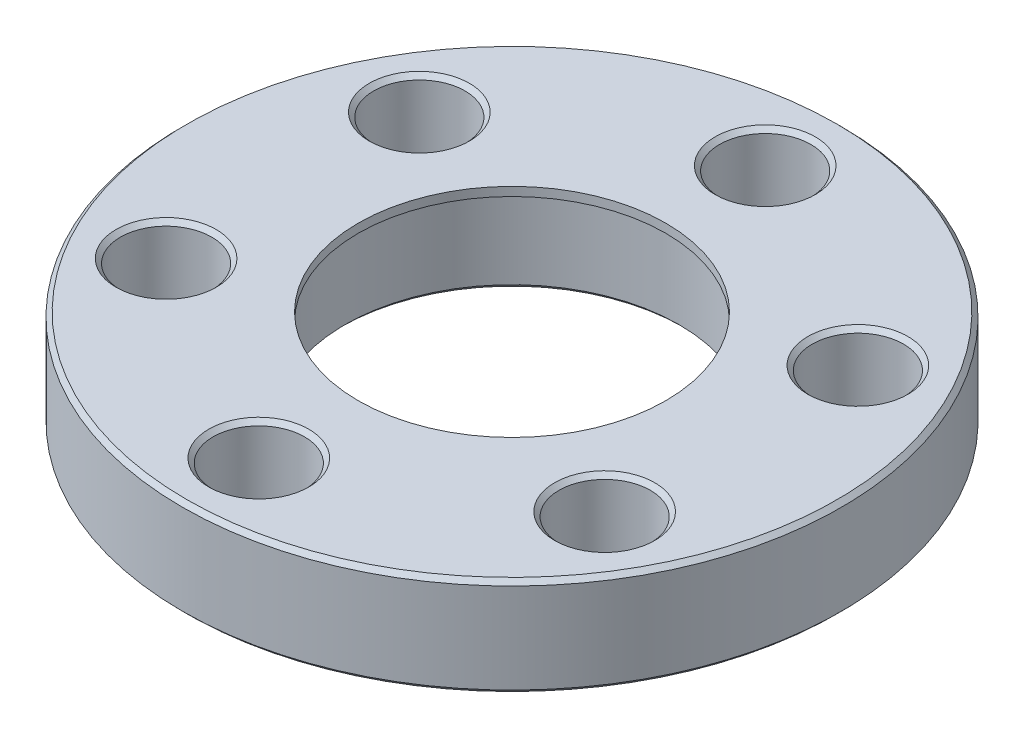
SolidWorks part; units mm, degrees
ref_plane "前视基准面" through (0, 0, 0) normal (0, 0, 1) x (1, 0, 0)
ref_plane "上视基准面" through (0, 0, 0) normal (0, 1, 0) x (1, 0, 0)
ref_plane "右视基准面" through (0, 0, 0) normal (1, 0, 0) x (0, 0, -1)
other "Configuration Table"
sketch "草图1" plane through (0, 0, 0) normal (0, 1, 0) x (1, 0, 0)
  circle A0 centre (0, 0) radius 7
  circle A1 centre (0, 0) radius 15
  circle A2 centre (0, 0) radius 11.525 construction
  circle A3 centre (0, 11.525) radius 2.08
  circle A4 centre (9.9809, 5.7625) radius 2.08
  circle A5 centre (9.9809, -5.7625) radius 2.08
  circle A6 centre (0, -11.525) radius 2.08
  circle A7 centre (-9.9809, -5.7625) radius 2.08
  circle A8 centre (-9.9809, 5.7625) radius 2.08
  point P19 (0, 0)
  dimension "D1" = 14
  dimension "D2" = 30
  dimension "D3" = 23.05
  dimension "D4" = 4.16
  dimension "D5" = 6
extrude "凸台-拉伸1" add sketch "草图1" along normal blind 3.1
sketch "草图2" plane through (0, 0, 0) normal (0, -1, 0) x (-1, 0, 0)
  circle A0 centre (0, 0) radius 7 construction
  circle A1 centre (0, 0) radius 15 construction
  circle A2 centre (0, 0) radius 7
  circle A3 centre (0, 0) radius 15
  circle A4 centre (0, 11.53) radius 0.9
  circle A6 centre (0, 0) radius 11.53 construction
  circle A7 centre (9.9853, 5.765) radius 0.9
  circle A8 centre (9.9853, -5.765) radius 0.9
  circle A9 centre (0, -11.53) radius 0.9
  circle A10 centre (-9.9853, -5.765) radius 0.9
  circle A11 centre (-9.9853, 5.765) radius 0.9
  point P21 (0, 0)
  dimension "D1" = 1.8
  dimension "D2" = 23.06
  dimension "D3" = 6
extrude "凸台-拉伸2" add sketch "草图2" along normal blind 1.4
sketch "草图3" plane through (0, -1.4, 0) normal (0, -1, 0) x (-1, 0, 0)
  circle A0 centre (0, 0) radius 7.6
  dimension "D1" = 15.2
extrude "切除-拉伸1" cut sketch "草图3" against normal blind 4.1
chamfer "倒角1" distance 0.2 angle 45 15 edges at (0, -1.4, -15) (-9.9809, 3.1, -3.6825) (0, 3.1, 13.605) (9.9809, 3.1, -3.6825) (0, 3.1, 15) (0, 3.1, -9.445) (9.9809, 3.1, 7.8425) (-9.9809, 3.1, 7.8425) (9.9853, -1.4, -6.665) (0, -1.4, 10.63) (-9.9853, -1.4, -6.665) (0, -1.4, -12.43) (-9.9853, -1.4, 4.865) (9.9853, -1.4, 4.865) (0, -1.4, -7.6)
chamfer "倒角2" distance 0.3 angle 45 1 edges at (0, 2.7, -7.6)
